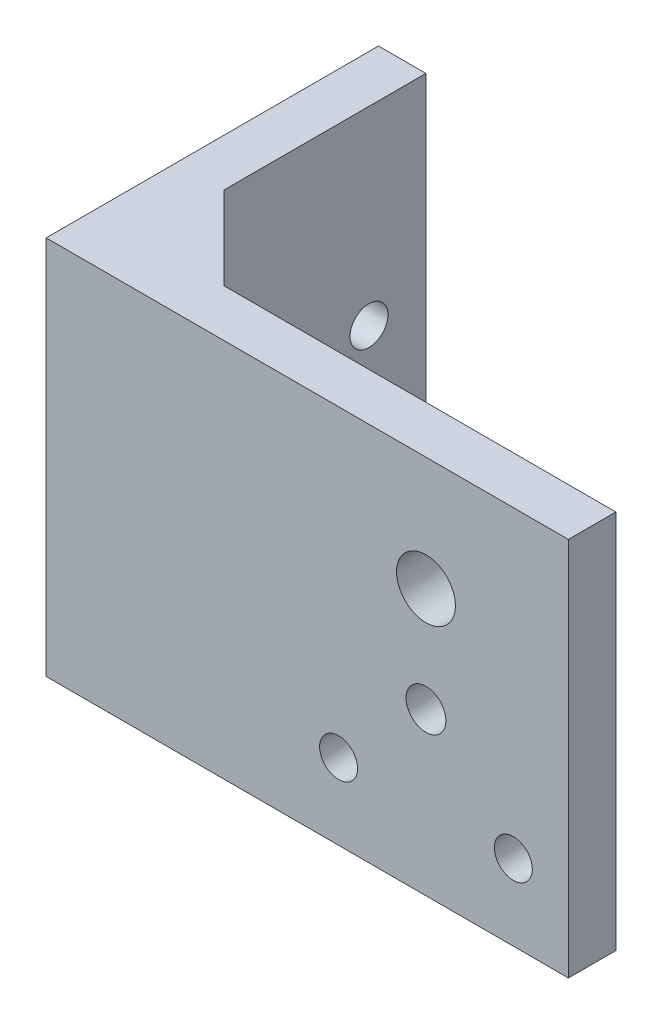
SolidWorks part; units mm, degrees
ref_plane "Front Plane" through (0, 0, 0) normal (0, 0, 1) x (1, 0, 0)
ref_plane "Top Plane" through (0, 0, 0) normal (0, 1, 0) x (1, 0, 0)
ref_plane "Right Plane" through (0, 0, 0) normal (1, 0, 0) x (0, 0, -1)
sketch "Sketch1" plane through (0, 0, 0) normal (0, 1, 0) x (1, 0, 0)
  line L0 (0, 0) -> (55, 0)
  line L1 (55, 0) -> (55, 5)
  line L4 (5, 35) -> (0, 35)
  line L5 (0, 35) -> (0, 0)
  line L6 (5, 35) -> (5, 13.75)
  line L11 (5, 13.75) -> (13.75, 5)
  line L12 (13.75, 5) -> (55, 5)
  dimension "D1" = 35
  dimension "D2" = 55
  dimension "D3" = 5
  dimension "D4" = 5
extrude "Boss-Extrude3" add sketch "Sketch1" along normal blind 40 contours L12 L1 L0 L5 L4 L6 L11
sketch "Sketch5" plane through (0, 0, 0) normal (0, -1, 0) x (1, 0, 0)
  line L0 (5, -13.75) -> (5, -5)
  line L1 (5, -5) -> (13.75, -5)
  line L2 (13.75, -5) -> (5, -13.75)
extrude "Cut-Extrude1" cut sketch "Sketch5" against normal blind 35 contours L2 L0 L1
sketch "Sketch6" plane through (0, 0, 0) normal (0, -1, 0) x (1, 0, 0)
  line L0 (13.75, -5) -> (5, -13.75)
  line L1 (5, -13.75) -> (5, -5)
  line L2 (5, -5) -> (13.75, -5)
extrude "Boss-Extrude4" add sketch "Sketch6" against normal blind 5 contours L2 L0 L1
sketch "Sketch7" plane through (0, 0, -5) normal (0, 0, -1) x (-1, 0, 0)
  line L2 (-13.75, 0) -> (-55, 0) construction
  line L4 (-55, 40) -> (-55, 0) construction
  line L5 (-13.75, 40) -> (-55, 40) construction
  circle A4 centre (-40, 28) radius 3.1
  circle A5 centre (-40, 17) radius 2.1
  circle A6 centre (-49.2, 8) radius 2
  circle A7 centre (-30.8, 8) radius 2
  point P2 (-48.825, 2.6661)
  point P10 (0, 0)
  dimension "D1" = 4
  dimension "D2" = 18.4
  dimension "D5" = 5.8
  dimension "D6" = 4.2
  dimension "D7" = 12
  dimension "D9" = 11
  dimension "D3" = 6.2
  dimension "D4" = 8
  dimension "D8" = 15
extrude "Cut-Extrude9" cut sketch "Sketch7" against normal through all contours A4 | A6 | A5 | A7
sketch "Sketch16" plane through (5, 0, 0) normal (1, 0, 0) x (0, 0, -1)
  line L7 (5, 0) -> (13.75, 0) construction
  line L8 (5, 35) -> (5, 5) construction
  line L9 (13.75, 40) -> (5, 40) construction
  circle A0 centre (29, 20) radius 2
  circle A1 centre (11, 31) radius 2
  circle A2 centre (11, 9) radius 2
  dimension "D1" = 9
  dimension "D2" = 6
  dimension "D3" = 6
  dimension "D4" = 9
extrude "Cut-Extrude12" cut sketch "Sketch16" against normal through all contours A1 | A0 | A2
